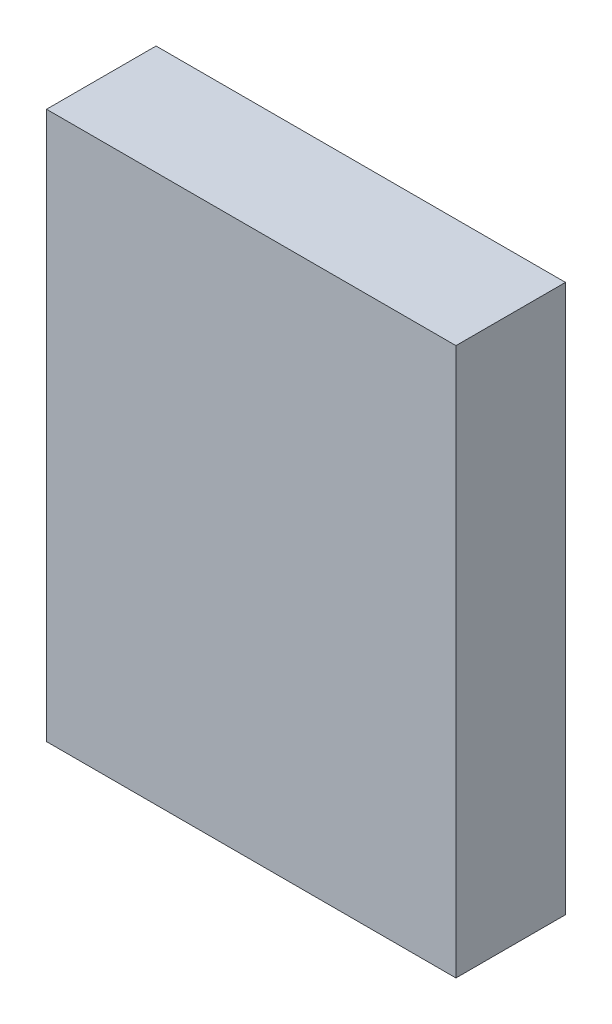
SolidWorks part; units mm, degrees
ref_plane "Спереди" through (0, 0, 0) normal (0, 0, 1) x (1, 0, 0)
ref_plane "Сверху" through (0, 0, 0) normal (0, 1, 0) x (1, 0, 0)
ref_plane "Справа" through (0, 0, 0) normal (1, 0, 0) x (0, 0, -1)
sketch "Эскиз5" plane through (0, 0, 0) normal (0, 0, 1) x (1, 0, 0)
  line L1 (-18.689, -25) -> (18.689, -25)
  line L2 (-18.689, -25) -> (-18.689, 25)
  line L3 (-18.689, 25) -> (18.689, 25)
  line L4 (18.689, -25) -> (18.689, 25)
  line L5 (-18.689, -25) -> (18.689, 25) construction
  line L6 (-18.689, 25) -> (18.689, -25) construction
  point P0 (0, 0)
extrude "Бобышка-Вытянуть2" add sketch "Эскиз5" along normal blind 10 contours L2 L3 L4 L1
sketch "ангренажный мост" plane through (0, 0, 10) normal (0, 0, 1) x (1, 0, 0)
  line L0 (-7.8996, -16.334) -> (-3.787, -11.9127)
  line L1 (1.1069, -9.3047) -> (3.4546, -11.6681)
  line L2 (3.9401, -11.9208) -> (8.2701, -12.6678)
  line L3 (9.4343, -11.4735) -> (9.7159, -10.401)
  line L4 (10.2173, -9.77) -> (11.3033, -9.1983)
  line L5 (11.6059, -14.0549) -> (8.4903, -14.3541)
  line L6 (8.3946, -14.3053) -> (-2.7438, -15.3749)
  line L7 (-2.7438, -15.3749) -> (-5.959, -18.794)
  line L8 (-5.9854, -20.5913) -> (-5.6833, -22.7215)
  line L9 (-5.8831, -23.4496) -> (-6.3288, -24.0048)
  line L10 (-11.3637, -19.8827) -> (-8.0539, -16.3245)
  line L11 (9.3569, -11.7683) -> (9.2937, -12.0094)
  line L12 (9.3569, -0.7683) -> (9.2937, -1.0094)
  line L13 (9.4343, -0.4735) -> (9.7159, 0.599)
  line L14 (10.2173, 1.23) -> (11.3033, 1.8017)
  line L15 (11.6059, -3.0549) -> (8.4903, -3.3541)
  line L16 (8.3946, -3.3053) -> (-2.7438, -4.3749)
  line L17 (-2.7438, -4.3749) -> (-5.959, -7.794)
  line L18 (-5.9854, -9.5913) -> (-5.6833, -11.7215)
  line L19 (-5.8831, -12.4496) -> (-6.3288, -13.0048)
  line L20 (-11.3637, -8.8827) -> (-8.0539, -5.3245)
  line L21 (-7.8996, -5.334) -> (-3.787, -0.9127)
  line L22 (1.1069, 1.6953) -> (3.4546, -0.6681)
  line L23 (3.9401, -0.9208) -> (8.2701, -1.6678)
  line L24 (9.3569, 10.2317) -> (9.2937, 9.9906)
  line L25 (9.4343, 10.5265) -> (9.7159, 11.599)
  line L26 (10.2173, 12.23) -> (11.3033, 12.8017)
  line L27 (11.6059, 7.9451) -> (8.4903, 7.6459)
  line L28 (8.3946, 7.6947) -> (-2.7438, 6.6251)
  line L29 (-2.7438, 6.6251) -> (-5.959, 3.206)
  line L30 (-5.9854, 1.4087) -> (-5.6833, -0.7215)
  line L31 (-5.8831, -1.4496) -> (-6.3288, -2.0048)
  line L32 (-11.3637, 2.1173) -> (-8.0539, 5.6755)
  line L33 (-7.8996, 5.666) -> (-3.787, 10.0873)
  line L34 (1.1069, 12.6953) -> (3.4546, 10.3319)
  line L35 (3.9401, 10.0792) -> (8.2701, 9.3322)
  line L36 (9.3569, 21.2317) -> (9.2937, 20.9906)
  line L37 (9.4343, 21.5265) -> (9.7159, 22.599)
  line L38 (10.2173, 23.23) -> (11.3033, 23.8017)
  line L39 (11.6059, 18.9451) -> (8.4903, 18.6459)
  line L40 (8.3946, 18.6947) -> (-2.7438, 17.6251)
  line L41 (-2.7438, 17.6251) -> (-5.959, 14.206)
  line L42 (-5.9854, 12.4087) -> (-5.6833, 10.2785)
  line L43 (-5.8831, 9.5504) -> (-6.3288, 8.9952)
  line L44 (-11.3637, 13.1173) -> (-8.0539, 16.6755)
  line L45 (-7.8996, 16.666) -> (-3.787, 21.0873)
  line L46 (1.1069, 23.6953) -> (3.4546, 21.3319)
  line L47 (3.9401, 21.0792) -> (8.2701, 20.3322)
  arc A17 (-11.3637, -19.8827) -> (-9.4971, -21.9436) centre (-1.0368, -12.4049) ccw
  arc A18 (-8.0539, -16.3245) -> (-7.8996, -16.334) centre (-7.9728, -16.2659) ccw
  arc A19 (-3.787, -11.9127) -> (-1.6906, -11.5403) centre (-3.7358, -6.1129) ccw
  arc A20 (9.1133, -1.3586) -> (9.2937, -1.0094) centre (8.4232, -0.7809) ccw
  arc A21 (-1.2128, -11.3353) -> (1.1069, -9.3047) centre (-3.7358, -6.1129) ccw
  arc A22 (3.4546, -11.6681) -> (3.9401, -11.9208) centre (4.0932, -11.0339) ccw
  arc A23 (8.2701, -12.6678) -> (8.9443, -12.5146) centre (8.4232, -11.7809) ccw
  arc A24 (10.2173, 1.23) -> (9.7159, 0.599) centre (10.6832, 0.3451) ccw
  arc A25 (10.2173, -9.77) -> (9.7159, -10.401) centre (10.6832, -10.6549) ccw
  arc A26 (11.6059, -14.0549) -> (11.3033, -9.1983) centre (-1.0368, -12.4049) ccw
  arc A27 (8.4903, -14.3541) -> (8.3946, -14.3053) centre (8.4042, -14.4049) ccw
  arc A28 (-5.959, -18.794) -> (-5.9854, -20.5913) centre (-0.2428, -19.7769) ccw
  arc A29 (-5.8831, -23.4496) -> (-5.6833, -22.7215) centre (-6.6238, -22.8549) ccw
  arc A30 (-8.0552, -23.0493) -> (-6.3288, -24.0048) centre (-1.0368, -12.4049) ccw
  arc A31 (-8.0552, -23.0493) -> (-9.4971, -21.9436) centre (-8.5218, -22.1649) ccw
  arc A44 (11.6059, -3.0549) -> (11.3033, 1.8017) centre (-1.0368, -1.4049) ccw
  arc A51 (9.1133, -12.3586) -> (9.2937, -12.0094) centre (8.4232, -11.7809) ccw
  arc A52 (8.4903, -3.3541) -> (8.3946, -3.3053) centre (8.4042, -3.4049) ccw
  arc A53 (-5.959, -7.794) -> (-5.9854, -9.5913) centre (-0.2428, -8.7769) ccw
  arc A54 (-5.8831, -12.4496) -> (-5.6833, -11.7215) centre (-6.6238, -11.8549) ccw
  arc A55 (-8.0552, -12.0493) -> (-6.3288, -13.0048) centre (-1.0368, -1.4049) ccw
  arc A56 (-8.0552, -12.0493) -> (-9.4971, -10.9436) centre (-8.5218, -11.1649) ccw
  arc A57 (-11.3637, -8.8827) -> (-9.4971, -10.9436) centre (-1.0368, -1.4049) ccw
  arc A58 (-8.0539, -5.3245) -> (-7.8996, -5.334) centre (-7.9728, -5.2659) ccw
  arc A59 (-3.787, -0.9127) -> (-1.6906, -0.5403) centre (-3.7358, 4.8871) ccw
  arc A60 (-1.2128, -0.3353) -> (1.1069, 1.6953) centre (-3.7358, 4.8871) ccw
  arc A61 (3.4546, -0.6681) -> (3.9401, -0.9208) centre (4.0932, -0.0339) ccw
  arc A62 (8.2701, -1.6678) -> (8.9443, -1.5146) centre (8.4232, -0.7809) ccw
  arc A63 (9.1133, 9.6414) -> (9.2937, 9.9906) centre (8.4232, 10.2191) ccw
  arc A64 (10.2173, 12.23) -> (9.7159, 11.599) centre (10.6832, 11.3451) ccw
  arc A65 (11.6059, 7.9451) -> (11.3033, 12.8017) centre (-1.0368, 9.5951) ccw
  arc A66 (8.4903, 7.6459) -> (8.3946, 7.6947) centre (8.4042, 7.5951) ccw
  arc A67 (-5.959, 3.206) -> (-5.9854, 1.4087) centre (-0.2428, 2.2231) ccw
  arc A68 (-5.8831, -1.4496) -> (-5.6833, -0.7215) centre (-6.6238, -0.8549) ccw
  arc A69 (-8.0552, -1.0493) -> (-6.3288, -2.0048) centre (-1.0368, 9.5951) ccw
  arc A70 (-8.0552, -1.0493) -> (-9.4971, 0.0564) centre (-8.5218, -0.1649) ccw
  arc A71 (-11.3637, 2.1173) -> (-9.4971, 0.0564) centre (-1.0368, 9.5951) ccw
  arc A72 (-8.0539, 5.6755) -> (-7.8996, 5.666) centre (-7.9728, 5.7341) ccw
  arc A73 (-3.787, 10.0873) -> (-1.6906, 10.4597) centre (-3.7358, 15.8871) ccw
  arc A74 (-1.2128, 10.6647) -> (1.1069, 12.6953) centre (-3.7358, 15.8871) ccw
  arc A75 (3.4546, 10.3319) -> (3.9401, 10.0792) centre (4.0932, 10.9661) ccw
  arc A76 (8.2701, 9.3322) -> (8.9443, 9.4854) centre (8.4232, 10.2191) ccw
  arc A77 (9.1133, 20.6414) -> (9.2937, 20.9906) centre (8.4232, 21.2191) ccw
  arc A78 (10.2173, 23.23) -> (9.7159, 22.599) centre (10.6832, 22.3451) ccw
  arc A79 (11.6059, 18.9451) -> (11.3033, 23.8017) centre (-1.0368, 20.5951) ccw
  arc A80 (8.4903, 18.6459) -> (8.3946, 18.6947) centre (8.4042, 18.5951) ccw
  arc A81 (-5.959, 14.206) -> (-5.9854, 12.4087) centre (-0.2428, 13.2231) ccw
  arc A82 (-5.8831, 9.5504) -> (-5.6833, 10.2785) centre (-6.6238, 10.1451) ccw
  arc A83 (-8.0552, 9.9507) -> (-6.3288, 8.9952) centre (-1.0368, 20.5951) ccw
  arc A84 (-8.0552, 9.9507) -> (-9.4971, 11.0564) centre (-8.5218, 10.8351) ccw
  arc A85 (-11.3637, 13.1173) -> (-9.4971, 11.0564) centre (-1.0368, 20.5951) ccw
  arc A86 (-8.0539, 16.6755) -> (-7.8996, 16.666) centre (-7.9728, 16.7341) ccw
  arc A87 (-3.787, 21.0873) -> (-1.6906, 21.4597) centre (-3.7358, 26.8871) ccw
  arc A88 (-1.2128, 21.6647) -> (1.1069, 23.6953) centre (-3.7358, 26.8871) ccw
  arc A89 (3.4546, 21.3319) -> (3.9401, 21.0792) centre (4.0932, 21.9661) ccw
  arc A90 (8.2701, 20.3322) -> (8.9443, 20.4854) centre (8.4232, 21.2191) ccw
  spline S0 degree 3 poles (9.4343, -0.4735) (9.4089, -0.5703) (9.3832, -0.6682) (9.3569, -0.7683) knots 0 0 0 0 1 1 1 1
  spline S1 degree 3 poles (-1.6906, -11.5403) (-1.6123, -11.5108) (-1.5305, -11.478) (-1.3682, -11.4084) (-1.2881, -11.3718) (-1.2128, -11.3353) knots 0 0 0 0 0.5 0.5 1 1 1 1
  spline S2 degree 3 poles (-1.6906, -0.5403) (-1.6123, -0.5108) (-1.5305, -0.478) (-1.3682, -0.4084) (-1.2881, -0.3718) (-1.2128, -0.3353) knots 0 0 0 0 0.5 0.5 1 1 1 1
  spline S3 degree 3 poles (9.1133, -1.3586) (9.0621, -1.4197) (9.0057, -1.471) (8.9443, -1.5146) knots 0 0 0 0 1 1 1 1
  spline S4 degree 3 poles (9.4343, 10.5265) (9.4089, 10.4297) (9.3832, 10.3318) (9.3569, 10.2317) knots 0 0 0 0 1 1 1 1
  spline S5 degree 3 poles (9.4343, -11.4735) (9.4089, -11.5703) (9.3832, -11.6682) (9.3569, -11.7683) knots 0 0 0 0 1 1 1 1
  spline S6 degree 3 poles (9.1133, -12.3586) (9.0621, -12.4197) (9.0057, -12.471) (8.9443, -12.5146) knots 0 0 0 0 1 1 1 1
  spline S7 degree 3 poles (-1.6906, 10.4597) (-1.6123, 10.4892) (-1.5305, 10.522) (-1.3682, 10.5916) (-1.2881, 10.6282) (-1.2128, 10.6647) knots 0 0 0 0 0.5 0.5 1 1 1 1
  spline S8 degree 3 poles (9.1133, 9.6414) (9.0621, 9.5803) (9.0057, 9.529) (8.9443, 9.4854) knots 0 0 0 0 1 1 1 1
  spline S9 degree 3 poles (9.4343, 21.5265) (9.4089, 21.4297) (9.3832, 21.3318) (9.3569, 21.2317) knots 0 0 0 0 1 1 1 1
  spline S10 degree 3 poles (-1.6906, 21.4597) (-1.6123, 21.4892) (-1.5305, 21.522) (-1.3682, 21.5916) (-1.2881, 21.6282) (-1.2128, 21.6647) knots 0 0 0 0 0.5 0.5 1 1 1 1
  spline S11 degree 3 poles (9.1133, 20.6414) (9.0621, 20.5803) (9.0057, 20.529) (8.9443, 20.4854) knots 0 0 0 0 1 1 1 1
  point P0 (0, 0)
  dimension "D1" = 4
sketch "под штифты и углы" plane through (0, 0, 10) normal (0, 0, 1) x (1, 0, 0)
  circle A0 centre (10.6832, -10.6549) radius 1
  circle A1 centre (-6.6238, -22.8549) radius 1
  circle A4 centre (-9.4971, -21.9436) radius 1
  circle A5 centre (-8.0552, -23.0493) radius 1
  circle A6 centre (9.7735, -9.5605) radius 1
  circle A7 centre (11.0975, -8.9025) radius 1
  circle A8 centre (11.8685, -14.5114) radius 1
  circle A9 centre (9.7735, 1.4395) radius 1
  circle A10 centre (11.0975, 2.0975) radius 1
  circle A11 centre (10.6832, 0.3451) radius 1
  circle A12 centre (11.8685, -3.5114) radius 1
  circle A13 centre (-9.4971, -10.9436) radius 1
  circle A14 centre (-8.0552, -12.0493) radius 1
  circle A15 centre (-6.6238, -11.8549) radius 1
  circle A16 centre (9.7735, 12.4395) radius 1
  circle A17 centre (11.0975, 13.0975) radius 1
  circle A18 centre (10.6832, 11.3451) radius 1
  circle A19 centre (11.8685, 7.4886) radius 1
  circle A20 centre (-9.4971, 0.0564) radius 1
  circle A21 centre (-8.0552, -1.0493) radius 1
  circle A22 centre (-6.6238, -0.8549) radius 1
  circle A23 centre (9.7735, 23.4395) radius 1
  circle A24 centre (11.0975, 24.0975) radius 1
  circle A25 centre (10.6832, 22.3451) radius 1
  circle A26 centre (11.8685, 18.4886) radius 1
  circle A27 centre (-9.4971, 11.0564) radius 1
  circle A28 centre (-8.0552, 9.9507) radius 1
  circle A29 centre (-6.6238, 10.1451) radius 1
  dimension "D1" = 4
sketch "сЪем" plane through (0, 0, 10) normal (0, 0, 1) x (1, 0, 0)
  line L0 (0, -32.2096) -> (0, 32.2096) construction
  line L1 (-1, -32.2096) -> (-1, 32.2096)
  line L2 (1, -32.2096) -> (1, 32.2096)
  arc A0 (-1, -32.2096) -> (1, -32.2096) centre (0, -32.2096) ccw
  arc A1 (1, 32.2096) -> (-1, 32.2096) centre (0, 32.2096) ccw
  point P2 (0, 0)
sketch "перлаж" plane through (0, 0, 10) normal (0, 0, 1) x (1, 0, 0)
  circle A0 centre (-10.5945, -20.0559) radius 1
  circle A1 centre (-9.4734, -20.898) radius 1
  circle A3 centre (-7.2312, -22.5823) radius 1
  circle A4 centre (-6.1101, -23.4244) radius 1
  circle A11 centre (-7.464, -20.763) radius 1
  circle A12 centre (-6.3429, -21.6052) radius 1
  circle A19 centre (-7.6968, -18.9438) radius 1
  circle A20 centre (-6.5757, -19.7859) radius 1
  circle A28 centre (-6.8085, -17.9666) radius 1
  circle A29 centre (-5.6874, -18.8088) radius 1
  circle A37 centre (-5.9202, -16.9895) radius 1
  circle A38 centre (-4.799, -17.8316) radius 1
  circle A46 centre (-5.0318, -16.0124) radius 1
  circle A47 centre (-3.9107, -16.8545) radius 1
  circle A55 centre (-4.1435, -15.0352) radius 1
  circle A56 centre (-3.0224, -15.8774) radius 1
  circle A64 centre (-3.2552, -14.0581) radius 1
  circle A65 centre (-2.1341, -14.9002) radius 1
  circle A73 centre (-2.3669, -13.081) radius 1
  circle A74 centre (-1.2458, -13.9231) radius 1
  circle A75 centre (-0.1247, -14.7652) radius 1
  circle A82 centre (-1.4786, -12.1038) radius 1
  circle A83 centre (-0.3575, -12.946) radius 1
  circle A84 centre (0.7636, -13.7881) radius 1
  circle A85 centre (1.8847, -14.6302) radius 1
  circle A91 centre (-0.5903, -11.1267) radius 1
  circle A92 centre (0.5308, -11.9688) radius 1
  circle A93 centre (1.6519, -12.8109) radius 1
  circle A94 centre (2.7731, -13.6531) radius 1
  circle A95 centre (3.8942, -14.4952) radius 1
  circle A101 centre (1.4191, -10.9917) radius 1
  circle A102 centre (2.5403, -11.8338) radius 1
  circle A103 centre (3.6614, -12.6759) radius 1
  circle A104 centre (4.7825, -13.5181) radius 1
  circle A105 centre (5.9036, -14.3602) radius 1
  circle A112 centre (4.5497, -11.6988) radius 1
  circle A113 centre (5.6708, -12.5409) radius 1
  circle A114 centre (6.7919, -13.383) radius 1
  circle A115 centre (7.913, -14.2252) radius 1
  circle A123 centre (7.6802, -12.4059) radius 1
  circle A124 centre (8.8013, -13.248) radius 1
  circle A125 centre (9.9224, -14.0902) radius 1
  circle A143 centre (11.6991, -12.1359) radius 1
  circle A151 centre (11.4663, -10.3166) radius 1
  circle A163 centre (-9.7062, -19.0788) radius 1
  circle A164 centre (-8.8179, -18.1017) radius 1
  circle A165 centre (-7.9296, -17.1245) radius 1
  circle A166 centre (-7.0413, -16.1474) radius 1
  circle A167 centre (-6.153, -15.1703) radius 1
  circle A168 centre (-5.2646, -14.1931) radius 1
  circle A169 centre (-4.3763, -13.216) radius 1
  circle A170 centre (-3.488, -12.2389) radius 1
  circle A171 centre (-2.5997, -11.2617) radius 1
  circle A180 centre (-4.9889, -24.2665) radius 1
  circle A181 centre (-3.8678, -25.1087) radius 1
  circle A182 centre (-2.7467, -25.9508) radius 1
  circle A183 centre (-1.6256, -26.7929) radius 1
  circle A184 centre (-0.5045, -27.635) radius 1
  circle A185 centre (-4.1006, -23.2894) radius 1
  circle A186 centre (-2.9795, -24.1315) radius 1
  circle A187 centre (-1.8584, -24.9736) radius 1
  circle A188 centre (-0.7373, -25.8158) radius 1
  circle A189 centre (0.3838, -26.6579) radius 1
  circle A190 centre (-3.2123, -22.3123) radius 1
  circle A191 centre (-2.0912, -23.1544) radius 1
  circle A192 centre (-0.9701, -23.9965) radius 1
  circle A193 centre (0.151, -24.8386) radius 1
  circle A194 centre (1.2721, -25.6807) radius 1
  circle A195 centre (-3.4451, -20.493) radius 1
  circle A196 centre (-2.324, -21.3351) radius 1
  circle A197 centre (-1.2029, -22.1773) radius 1
  circle A198 centre (-0.0818, -23.0194) radius 1
  circle A199 centre (1.0393, -23.8615) radius 1
  circle A200 centre (2.1604, -24.7036) radius 1
  circle A201 centre (-0.3146, -21.2001) radius 1
  circle A202 centre (0.8065, -22.0422) radius 1
  circle A203 centre (1.9276, -22.8844) radius 1
  circle A204 centre (3.0487, -23.7265) radius 1
  circle A205 centre (1.6948, -21.0651) radius 1
  circle A206 centre (2.8159, -21.9072) radius 1
  circle A207 centre (3.9371, -22.7493) radius 1
  circle A208 centre (3.7043, -20.9301) radius 1
  circle A209 centre (-4.5662, -19.6509) radius 1
  circle A210 centre (-4.3334, -21.4701) radius 1
  circle A211 centre (0.5737, -20.223) radius 1
  circle A212 centre (0.3409, -18.4037) radius 1
  circle A213 centre (1.462, -19.2458) radius 1
  circle A214 centre (2.5831, -20.088) radius 1
  circle A215 centre (4.8254, -21.7722) radius 1
  circle A216 centre (0.1081, -16.5845) radius 1
  circle A217 centre (1.2292, -17.4266) radius 1
  circle A218 centre (2.3503, -18.2687) radius 1
  circle A219 centre (3.4715, -19.1108) radius 1
  circle A220 centre (4.5926, -19.953) radius 1
  circle A221 centre (5.7137, -20.7951) radius 1
  circle A222 centre (2.1175, -16.4495) radius 1
  circle A223 centre (3.2387, -17.2916) radius 1
  circle A224 centre (4.3598, -18.1337) radius 1
  circle A225 centre (5.4809, -18.9758) radius 1
  circle A226 centre (6.602, -19.8179) radius 1
  circle A227 centre (4.127, -16.3144) radius 1
  circle A228 centre (5.2481, -17.1566) radius 1
  circle A229 centre (6.3692, -17.9987) radius 1
  circle A230 centre (7.4903, -18.8408) radius 1
  circle A231 centre (6.1364, -16.1794) radius 1
  circle A232 centre (7.2575, -17.0216) radius 1
  circle A233 centre (8.3786, -17.8637) radius 1
  circle A234 centre (-3.6779, -18.6738) radius 1
  circle A235 centre (-2.5568, -19.5159) radius 1
  circle A236 centre (-1.4357, -20.358) radius 1
  circle A237 centre (-2.7896, -17.6966) radius 1
  circle A238 centre (-1.6685, -18.5387) radius 1
  circle A239 centre (-0.5474, -19.3809) radius 1
  circle A240 centre (-1.9013, -16.7195) radius 1
  circle A241 centre (-0.7802, -17.5616) radius 1
  circle A242 centre (8.1458, -16.0444) radius 1
  circle A243 centre (10.1552, -15.9094) radius 1
  circle A244 centre (9.2669, -16.8865) radius 1
  circle A245 centre (13.4757, -10.1816) radius 1
  circle A246 centre (13.7085, -12.0009) radius 1
  circle A247 centre (14.5968, -11.0237) radius 1
  circle A248 centre (3.8513, -6.241) radius 1
  circle A249 centre (4.7396, -5.2639) radius 1
  circle A250 centre (5.8607, -6.106) radius 1
  circle A251 centre (5.6279, -4.2868) radius 1
  circle A252 centre (6.749, -5.1289) radius 1
  circle A253 centre (7.8701, -5.971) radius 1
  circle A254 centre (2.7302, -5.3989) radius 1
  circle A255 centre (3.6185, -4.4218) radius 1
  circle A256 centre (4.5068, -3.4446) radius 1
  circle A257 centre (2.963, -7.2182) radius 1
  circle A258 centre (4.9724, -7.0832) radius 1
  circle A259 centre (6.9818, -6.9481) radius 1
  circle A260 centre (8.1029, -7.7903) radius 1
  circle A261 centre (8.9912, -6.8131) radius 1
  circle A262 centre (10.1124, -7.6552) radius 1
  circle A263 centre (0.9535, -7.3532) radius 1
  circle A264 centre (1.8419, -6.376) radius 1
  circle A265 centre (0.0652, -8.3303) radius 1
  circle A266 centre (2.0747, -8.1953) radius 1
  circle A267 centre (4.0841, -8.0603) radius 1
  circle A268 centre (6.0935, -7.9253) radius 1
  circle A269 centre (-0.8231, -9.3074) radius 1
  circle A270 centre (-1.7114, -10.2846) radius 1
  circle A271 centre (3.1958, -9.0374) radius 1
  circle A272 centre (4.3169, -9.8795) radius 1
  circle A273 centre (5.2052, -8.9024) radius 1
  circle A274 centre (7.2146, -8.7674) radius 1
  circle A275 centre (9.224, -8.6324) radius 1
  circle A276 centre (11.2335, -8.4974) radius 1
  circle A277 centre (5.438, -10.7217) radius 1
  circle A278 centre (6.3263, -9.7445) radius 1
  circle A279 centre (8.3357, -9.6095) radius 1
  circle A280 centre (7.4474, -10.5867) radius 1
  circle A281 centre (6.5591, -11.5638) radius 1
  circle A282 centre (8.5685, -11.4288) radius 1
  circle A283 centre (9.6896, -12.2709) radius 1
  circle A284 centre (-8.5851, -19.9209) radius 1
  circle A285 centre (11.9319, -13.9551) radius 1
  circle A286 centre (10.3452, -9.4745) radius 1
  circle A287 centre (12.3546, -9.3395) radius 1
  circle A288 centre (9.4568, -10.4516) radius 1
  circle A289 centre (-8.3523, -21.7402) radius 1
  circle A290 centre (0.9964, -15.6073) radius 1
  circle A291 centre (3.0059, -15.4723) radius 1
  circle A292 centre (5.0153, -15.3373) radius 1
  circle A293 centre (7.0247, -15.2023) radius 1
  circle A294 centre (9.0341, -15.0673) radius 1
  circle A295 centre (11.0436, -14.9323) radius 1
  circle A296 centre (12.5874, -11.1587) radius 1
  circle A297 centre (12.8202, -12.978) radius 1
  circle A298 centre (10.8108, -13.113) radius 1
  circle A299 centre (11.1199, -13.3961) radius 1
  circle A300 centre (10.578, -11.2938) radius 1
  circle A301 centre (10.0957, -10.635) radius 1
  circle A302 centre (1.1863, -9.1724) radius 1
  circle A303 centre (2.3075, -10.0146) radius 1
  circle A304 centre (3.4286, -10.8567) radius 1
  circle A305 centre (0.298, -10.1496) radius 1
  circle A306 centre (0.7998, -9.9463) radius 1
  circle A307 centre (-5.2217, -22.4473) radius 1
  circle A308 centre (-5.4545, -20.628) radius 1
  circle A309 centre (-1.013, -15.7424) radius 1
  dimension "D1" = 10
  dimension "D2" = 18
sketch "мост с отверстиями" plane through (0, 0, 10) normal (0, 0, 1) x (1, 0, 0)
  line L0 (-7.8973, -16.3331) -> (-3.7847, -11.9118)
  line L1 (1.1093, -9.3038) -> (3.457, -11.6673)
  line L2 (3.9425, -11.9199) -> (8.2725, -12.6669)
  line L3 (9.4367, -11.4727) -> (9.7183, -10.4001)
  line L4 (10.2197, -9.7691) -> (11.3057, -9.1974)
  line L5 (11.6083, -14.054) -> (8.4926, -14.3532)
  line L6 (8.3969, -14.3045) -> (-2.7415, -15.374)
  line L7 (-2.7415, -15.374) -> (-5.9566, -18.7931)
  line L8 (-5.983, -20.5905) -> (-5.6809, -22.7206)
  line L9 (-5.8807, -23.4488) -> (-6.3264, -24.0039)
  line L10 (-11.3614, -19.8819) -> (-8.0515, -16.3236)
  line L11 (9.3593, -11.7675) -> (9.296, -12.0086)
  circle A0 centre (-8.6845, -18.404) radius 0.3625
  circle A1 centre (6.5655, -13.454) radius 0.33
  circle A2 centre (-4.8075, -15.436) radius 1.0839
  circle A3 centre (-9.0765, -20.054) radius 1.1232
  circle A4 centre (10.6855, -10.654) radius 0.4
  circle A5 centre (-6.6215, -22.854) radius 0.4
  circle A6 centre (3.8625, -13.142) radius 1.0839
  circle A7 centre (-7.1845, -18.004) radius 0.33
  circle A8 centre (7.9655, -13.604) radius 0.3625
  circle A9 centre (-4.8075, -15.436) radius 0.7731
  circle A10 centre (-4.8075, -15.436) radius 0.53
  circle A11 centre (-1.0345, -12.404) radius 0.7731
  circle A12 centre (-1.0345, -12.404) radius 0.53
  circle A13 centre (3.8625, -13.142) radius 0.7731
  circle A14 centre (3.8625, -13.142) radius 0.53
  circle A15 centre (-9.0765, -20.054) radius 0.45
  circle A16 centre (10.0645, -12.404) radius 0.45
  arc A17 (-11.3614, -19.8819) -> (-9.4947, -21.9427) centre (-1.0345, -12.404) ccw
  arc A18 (-8.0515, -16.3236) -> (-7.8973, -16.3331) centre (-7.9705, -16.265) ccw
  arc A19 (-3.7847, -11.9118) -> (-1.6882, -11.5394) centre (-3.7335, -6.112) ccw
  arc A20 (-1.6882, -11.5394) -> (-1.2104, -11.3345) centre (-1.0345, -12.404) ccw
  arc A21 (-1.2104, -11.3345) -> (1.1093, -9.3038) centre (-3.7335, -6.112) ccw
  arc A22 (3.457, -11.6673) -> (3.9425, -11.9199) centre (4.0955, -11.033) ccw
  arc A23 (8.2725, -12.6669) -> (8.9467, -12.5138) centre (8.4255, -11.78) ccw
  arc A24 (8.9467, -12.5138) -> (9.4367, -11.4727) centre (10.0645, -12.404) ccw
  arc A25 (10.2197, -9.7691) -> (9.7183, -10.4001) centre (10.6855, -10.654) ccw
  arc A26 (11.6083, -14.054) -> (11.3057, -9.1974) centre (-1.0345, -12.404) ccw
  arc A27 (8.4926, -14.3532) -> (8.3969, -14.3045) centre (8.4065, -14.404) ccw
  arc A28 (-5.9566, -18.7931) -> (-5.983, -20.5905) centre (-0.2405, -19.776) ccw
  arc A29 (-5.8807, -23.4488) -> (-5.6809, -22.7206) centre (-6.6215, -22.854) ccw
  arc A30 (-8.0529, -23.0485) -> (-6.3264, -24.0039) centre (-1.0345, -12.404) ccw
  arc A31 (-8.0529, -23.0485) -> (-9.4947, -21.9427) centre (-8.5195, -22.164) ccw
  arc A32 (-10.0265, -20.054) -> (-8.1265, -20.054) centre (-9.0765, -20.054) ccw
  arc A33 (-8.1265, -20.054) -> (-10.0265, -20.054) centre (-9.0765, -20.054) ccw
  arc A34 (-8.947, -18.404) -> (-8.422, -18.404) centre (-8.6845, -18.404) ccw
  arc A35 (-8.422, -18.404) -> (-8.947, -18.404) centre (-8.6845, -18.404) ccw
  arc A36 (-6.8845, -18.004) -> (-7.1845, -17.704) centre (-7.1845, -18.004) ccw
  arc A37 (-4.8075, -14.436) -> (-4.8075, -16.436) centre (-4.8075, -15.436) ccw
  arc A38 (-4.8075, -16.436) -> (-4.8075, -14.436) centre (-4.8075, -15.436) ccw
  arc A39 (-1.0345, -11.404) -> (-1.0345, -13.404) centre (-1.0345, -12.404) ccw
  arc A40 (-1.0345, -13.404) -> (-1.0345, -11.404) centre (-1.0345, -12.404) ccw
  arc A41 (3.8625, -12.142) -> (3.8625, -14.142) centre (3.8625, -13.142) ccw
  arc A42 (3.8625, -14.142) -> (3.8625, -12.142) centre (3.8625, -13.142) ccw
  arc A43 (6.8655, -13.454) -> (6.5655, -13.154) centre (6.5655, -13.454) ccw
  arc A44 (9.1156, -12.3577) -> (9.3593, -11.7675) centre (10.0645, -12.404) ccw
  arc A45 (-5.3075, -15.436) -> (-4.3075, -15.436) centre (-4.8075, -15.436) ccw
  arc A46 (-4.3075, -15.436) -> (-5.3075, -15.436) centre (-4.8075, -15.436) ccw
  arc A47 (-1.5345, -12.404) -> (-0.5345, -12.404) centre (-1.0345, -12.404) ccw
  arc A48 (-0.5345, -12.404) -> (-1.5345, -12.404) centre (-1.0345, -12.404) ccw
  arc A49 (3.3625, -13.142) -> (4.3625, -13.142) centre (3.8625, -13.142) ccw
  arc A50 (4.3625, -13.142) -> (3.3625, -13.142) centre (3.8625, -13.142) ccw
  arc A51 (9.1156, -12.3577) -> (9.296, -12.0086) centre (8.4255, -11.78) ccw
  spline S0 degree 3 poles (-7.1845, -17.704) (-7.2434, -17.704) (-7.3022, -17.7219) (-7.4001, -17.7873) (-7.4391, -17.8348) (-7.4842, -17.9436) (-7.4902, -18.0048) (-7.4672, -18.1203) (-7.4383, -18.1745) (-7.355, -18.2578) (-7.3008, -18.2868) (-7.1853, -18.3098) (-7.1241, -18.3037) (-7.0153, -18.2586) (-6.9678, -18.2197) (-6.9023, -18.1217) (-6.8845, -18.0629) (-6.8845, -18.004) knots 0 0 0 0 0.125 0.125 0.25 0.25 0.375 0.375 0.5 0.5 0.625 0.625 0.75 0.75 0.875 0.875 1 1 1 1
  spline S1 degree 3 poles (-1.6882, -11.5394) (-1.6099, -11.5099) (-1.5282, -11.4771) (-1.3659, -11.4075) (-1.2858, -11.3709) (-1.2104, -11.3345) knots 0 0 0 0 0.5 0.5 1 1 1 1
  spline S2 degree 3 poles (6.5655, -13.154) (6.5066, -13.154) (6.4478, -13.1719) (6.3499, -13.2373) (6.3109, -13.2848) (6.2658, -13.3936) (6.2598, -13.4548) (6.2828, -13.5703) (6.3117, -13.6245) (6.395, -13.7078) (6.4492, -13.7368) (6.5647, -13.7598) (6.6259, -13.7537) (6.7347, -13.7086) (6.7822, -13.6697) (6.8477, -13.5717) (6.8655, -13.5129) (6.8655, -13.454) knots 0 0 0 0 0.125 0.125 0.25 0.25 0.375 0.375 0.5 0.5 0.625 0.625 0.75 0.75 0.875 0.875 1 1 1 1
  spline S3 degree 3 poles (7.703, -13.604) (7.703, -13.6436) (7.7124, -13.6841) (7.7472, -13.7551) (7.7735, -13.7873) (7.8359, -13.8357) (7.8738, -13.8531) (7.9125, -13.8611) (7.9471, -13.8682) (7.9839, -13.8682) (8.0185, -13.8611) (8.0572, -13.8531) (8.095, -13.8358) (8.1574, -13.7874) (8.1837, -13.7553) (8.2186, -13.6843) (8.228, -13.6437) (8.228, -13.604) knots 0.5 0.5 0.5 0.5 0.5726 0.5726 0.645049 0.645049 0.717649 0.717649 0.717649 0.782351 0.782351 0.782351 0.854887 0.854887 0.927269 0.927269 1 1 1 1
  spline S4 degree 3 poles (8.228, -13.604) (8.228, -13.5646) (8.2186, -13.5242) (8.184, -13.4532) (8.1578, -13.421) (8.0954, -13.3725) (8.0576, -13.355) (8.0188, -13.347) (7.984, -13.3398) (7.947, -13.3398) (7.9122, -13.347) (7.8734, -13.355) (7.8357, -13.3725) (7.7733, -13.4209) (7.7471, -13.4531) (7.7124, -13.524) (7.703, -13.5645) (7.703, -13.604) knots 0 0 0 0 0.072383 0.072383 0.144834 0.144834 0.217433 0.217433 0.217433 0.282567 0.282567 0.282567 0.355106 0.355106 0.427486 0.427486 0.5 0.5 0.5 0.5
  spline S5 degree 3 poles (9.4367, -11.4727) (9.4113, -11.5694) (9.3856, -11.6674) (9.3593, -11.7675) knots 0 0 0 0 1 1 1 1
  spline S6 degree 3 poles (9.1156, -12.3577) (9.0644, -12.4189) (9.0081, -12.4702) (8.9467, -12.5138) knots 0 0 0 0 1 1 1 1
